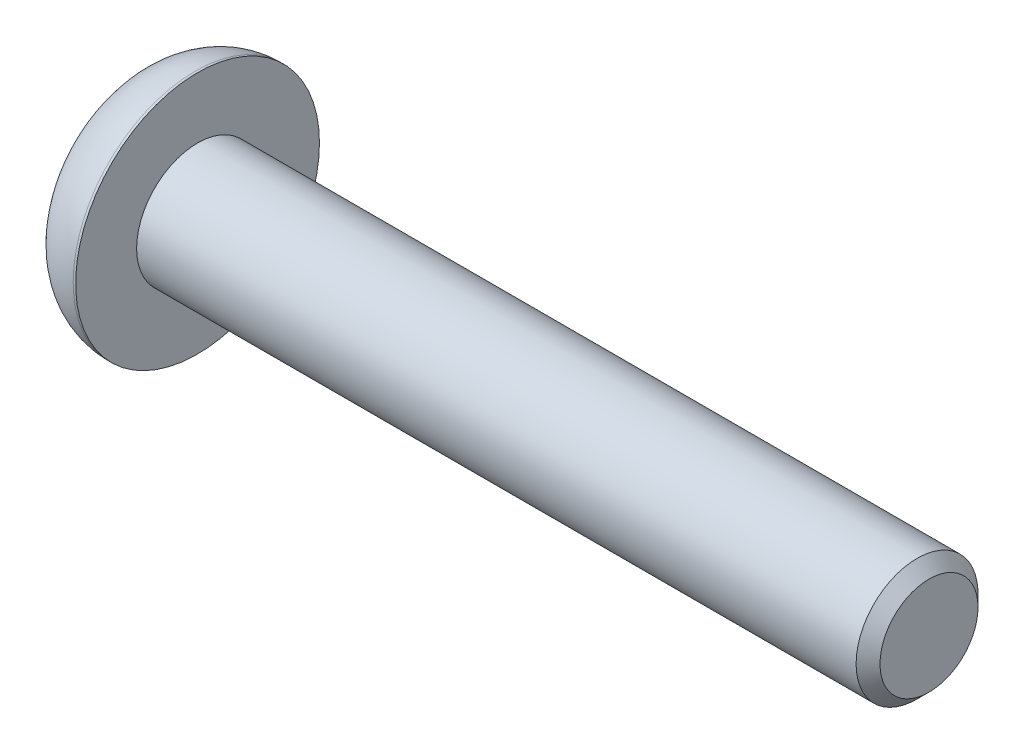
SolidWorks part; units mm, degrees
ref_plane "Front Plane" through (0, 0, 0) normal (0, 0, 1) x (1, 0, 0)
ref_plane "Top Plane" through (0, 0, 0) normal (0, 1, 0) x (1, 0, 0)
ref_plane "Right Plane" through (0, 0, 0) normal (1, 0, 0) x (0, 0, -1)
sketch "Sketch1" plane through (0, 0, 0) normal (0, 0, 1) x (1, 0, 0)
  line L0 (0, 5) -> (0, 0)
  line L1 (0, 0) -> (2.8, 0)
  line L2 (2.8, 0) -> (2.8, 5)
  line L3 (2.8, 5) -> (0, 5)
  line L4 (0, 0) -> (2.8, 0) construction
revolve "Revolve1" add sketch "Sketch1" angle 360 about L4
sketch "Sketch2" plane through (2.8, 0, 0) normal (1, 0, 0) x (0, 0, -1)
  circle A0 centre (0, 0) radius 2.5
extrude "Boss-Extrude1" add sketch "Sketch2" along normal blind 30
sketch "Sketch3" plane through (0, 0, 0) normal (-1, 0, 0) x (0, 0, 1)
  line L0 (1.5, -0.866) -> (1.5, 0.866)
  line L1 (1.5, 0.866) -> (0, 1.7321)
  line L2 (0, 1.7321) -> (-1.5, 0.866)
  line L3 (-1.5, 0.866) -> (-1.5, -0.866)
  line L4 (-1.5, -0.866) -> (0, -1.7321)
  line L5 (0, -1.7321) -> (1.5, -0.866)
extrude "Cut-Extrude1" cut sketch "Sketch3" against normal blind 1.82
hole_wizard "Ø3.0 (3) Diameter Hole1" positions "Sketch5" profile "Sketch4" hole size "Ø3.0" standard "ANSI Metric"
sketch "Sketch5" plane through (1.82, 0, 0) normal (-1, 0, 0) x (0, 0, 1)
  point P0 (0, 0)
sketch "Sketch4" plane through (1.82, 0, 0) normal (0, 1, 0) x (0, 0, 1)
  line L0 (0, 0) -> (0, 0.98)
  line L1 (0, 0.98) -> (1.5, 0.114)
  line L2 (1.5, 0.114) -> (1.5, 0)
  line L5 (1.5, 0) -> (0, 0)
  line L10 (0, 0.98) -> (-1.5, 0.114) construction
  line L11 (0, -6.35) -> (0, 107.95) construction
  dimension "Hole Dia." = 3
  dimension "Hole Depth" = 0.114
  dimension "Drill Angle" = 120
chamfer "Chamfer1" distance 0.4905 angle 45 1 edges at (32.8, 0, -2.5)
fillet "Fillet1" radius 2.7 1 edges at (0, 0, -5)
